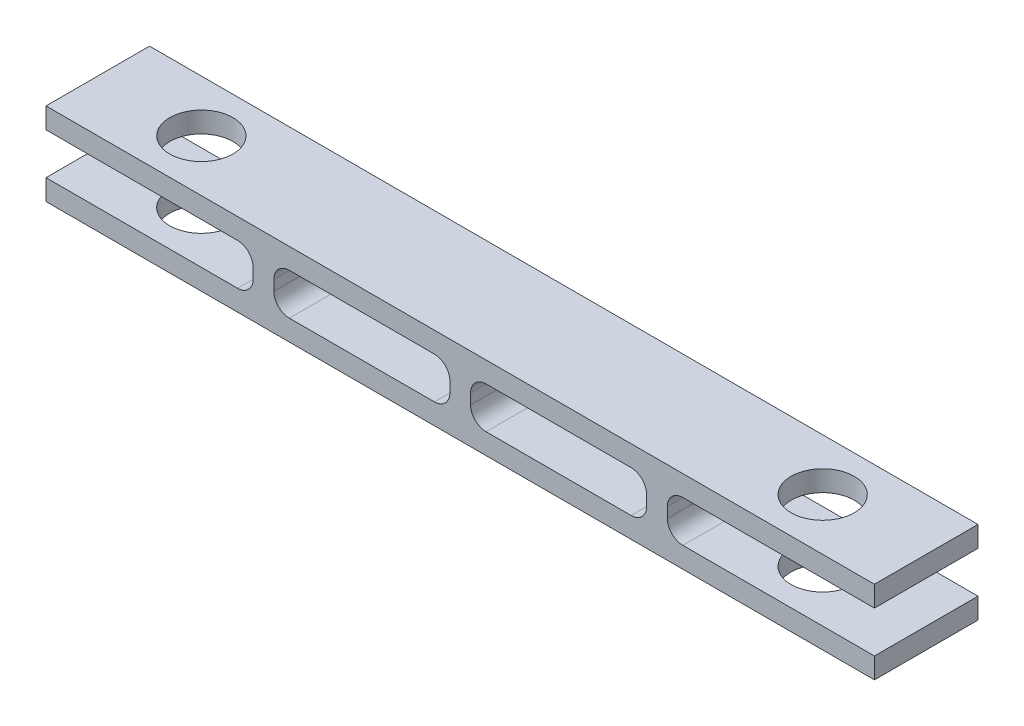
SolidWorks part; units mm, degrees
ref_plane "Front Plane" through (0, 0, 0) normal (0, 0, 1) x (1, 0, 0)
ref_plane "Top Plane" through (0, 0, 0) normal (0, 1, 0) x (1, 0, 0)
ref_plane "Right Plane" through (0, 0, 0) normal (1, 0, 0) x (0, 0, -1)
sketch "Sketch1" plane through (0, 0, 0) normal (0, 1, 0) x (1, 0, 0)
  line L1 (0, 0) -> (40, 0)
  line L2 (0, 0) -> (0, 5)
  line L3 (0, 5) -> (40, 5)
  line L4 (40, 0) -> (40, 5)
  dimension "D1" = 40
  dimension "D2" = 5
extrude "Boss-Extrude1" add sketch "Sketch1" along normal blind 4
sketch "Sketch2" plane through (0, 4, 0) normal (0, 1, 0) x (1, 0, 0)
  line L0 (0, 5) -> (0, 0) construction
  line L7 (20, 5) -> (20, 0) construction
  line L8 (40, 5) -> (0, 5) construction
  line L9 (0, 0) -> (40, 0) construction
  circle A0 centre (5, 2.5) radius 1.525
  circle A1 centre (35, 2.5) radius 1.525
  point P4 (0, 2.5)
  dimension "D1" = 3.05
  dimension "D2" = 5
extrude "Cut-Extrude1" cut sketch "Sketch2" against normal through all
sketch "Sketch3" plane through (0, 0, -5) normal (0, 0, -1) x (-1, 0, 0)
  line L0 (-40, 4) -> (-40, 0) construction
  line L1 (-40, 3) -> (-30, 3)
  line L2 (-40, 3) -> (-40, 1)
  line L3 (-40, 1) -> (-30, 1)
  line L4 (-30, 3) -> (-30, 1)
  line L5 (-20, 4) -> (-20, 0) construction
  line L6 (-29, 3) -> (-20.5, 3)
  line L7 (-29, 3) -> (-29, 1)
  line L8 (-29, 1) -> (-20.5, 1)
  line L9 (-20.5, 3) -> (-20.5, 1)
  line L14 (-40, 4) -> (0, 4) construction
  line L15 (-40, 0) -> (0, 0) construction
  line L16 (-19.5, 3) -> (-19.5, 1)
  line L17 (-11, 1) -> (-19.5, 1)
  line L18 (-11, 3) -> (-11, 1)
  line L19 (-11, 3) -> (-19.5, 3)
  line L20 (-10, 3) -> (-10, 1)
  line L21 (0, 1) -> (-10, 1)
  line L22 (0, 3) -> (0, 1)
  line L23 (0, 3) -> (-10, 3)
  point P10 (-40, 2)
  point P11 (-40, 2)
  point P12 (-29, 2)
  point P13 (-30, 2)
  dimension "D1" = 10
  dimension "D2" = 2
  dimension "D3" = 1
  dimension "D4" = 8.5
extrude "Cut-Extrude2" cut sketch "Sketch3" against normal through all
fillet "Fillet1" radius 0.75 12 edges at (11, 1, -2.5) (20.5, 1, -2.5) (30, 1, -2.5) (30, 3, -2.5) (10, 1, -2.5) (19.5, 1, -2.5) (29, 1, -2.5) (11, 3, -2.5) (20.5, 3, -2.5) (10, 3, -2.5) (19.5, 3, -2.5) (29, 3, -2.5)
equation "\"columnWidth\"= 1"
equation "\"gapWidth\"= \"riserWidth\" / 2 - \"gapFromEdge\" - ( \"columnWidth\" * \"columnNumber\" )"
equation "\"columnNumber\"= 1.5"
equation "\"gapFromEdge\"= 10"
equation "\"riserWidth\"= 40"
equation "\"D1@Sketch1\"=\"riserWidth\""
equation "\"D1@Sketch3\"=\"gapFromEdge\""
equation "\"D3@Sketch3\"=\"columnWidth\""
equation "\"D4@Sketch3\"=\"gapWidth\""
